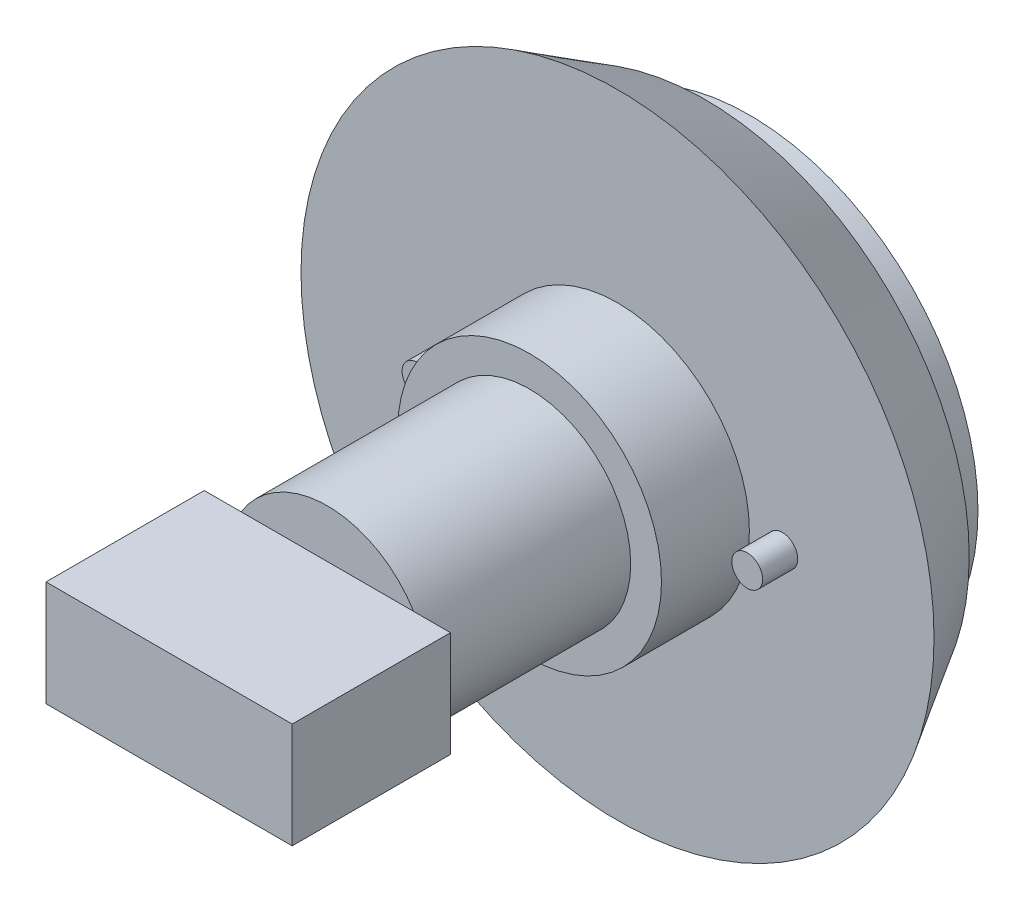
SolidWorks part; units mm, degrees
ref_plane "Front Plane" through (0, 0, 0) normal (0, 0, 1) x (1, 0, 0)
ref_plane "Top Plane" through (0, 0, 0) normal (0, 1, 0) x (1, 0, 0)
ref_plane "Right Plane" through (0, 0, 0) normal (1, 0, 0) x (0, 0, -1)
sketch "Sketch1" plane through (0, 0, 0) normal (0, 0, 1) x (1, 0, 0)
  circle A0 centre (0, 0) radius 26
  dimension "D1" = 52
extrude "Boss-Extrude1" add sketch "Sketch1" along normal blind 15
sketch "Sketch2" plane through (0, 0, 0) normal (0, 1, 0) x (1, 0, 0)
  line L0 (26, -15) -> (36, -15)
  line L1 (36, -15) -> (30, -5)
  line L2 (30, -5) -> (26, -5)
  line L3 (26, -15) -> (26, 0) construction
  line L4 (26, -5) -> (26, -15)
  line L5 (0, -15) -> (0, 0) construction
  dimension "D1" = 5
  dimension "D2" = 10
  dimension "D3" = 4
revolve "Revolve1" add sketch "Sketch2" angle 360 about L5
sketch "Sketch3" plane through (0, 0, 15) normal (0, 0, 1) x (1, 0, 0)
  circle A0 centre (0, 0) radius 15
  dimension "D1" = 30
extrude "Boss-Extrude2" add sketch "Sketch3" along normal blind 10
sketch "Sketch4" plane through (0, 0, 25) normal (0, 0, 1) x (1, 0, 0)
  circle A0 centre (0, 0) radius 11.5
  dimension "D1" = 23
extrude "Boss-Extrude3" add sketch "Sketch4" along normal blind 23
sketch "Sketch5" plane through (0, 0, 48) normal (0, 0, 1) x (1, 0, 0)
  line L0 (-11.5, 0) -> (11.5, 0) construction
  line L2 (-14, 6) -> (14, 6)
  line L3 (-14, 6) -> (-14, -6)
  line L4 (-14, -6) -> (14, -6)
  line L5 (14, 6) -> (14, -6)
  line L6 (-14, 6) -> (14, -6) construction
  line L7 (-14, -6) -> (14, 6) construction
  circle A0 centre (0, 0) radius 11.5 construction
  point P5 (0, 0)
  dimension "D1" = 28
  dimension "D2" = 12
extrude "Boss-Extrude4" add sketch "Sketch5" along normal blind 18
sketch "Sketch6" plane through (0, 0, 15) normal (0, 0, 1) x (1, 0, 0)
  line L0 (18.75, 0) -> (-18.75, 0) construction
  line L1 (0, 0) -> (0, -6) construction
  line L2 (-9.8107, -6) -> (9.8107, -6) construction
  circle A0 centre (-18.75, 0) radius 1.75
  circle A1 centre (18.75, 0) radius 1.75
  dimension "D1" = 3.5
  dimension "D2" = 18.75
extrude "Boss-Extrude5" add sketch "Sketch6" along normal blind 4
